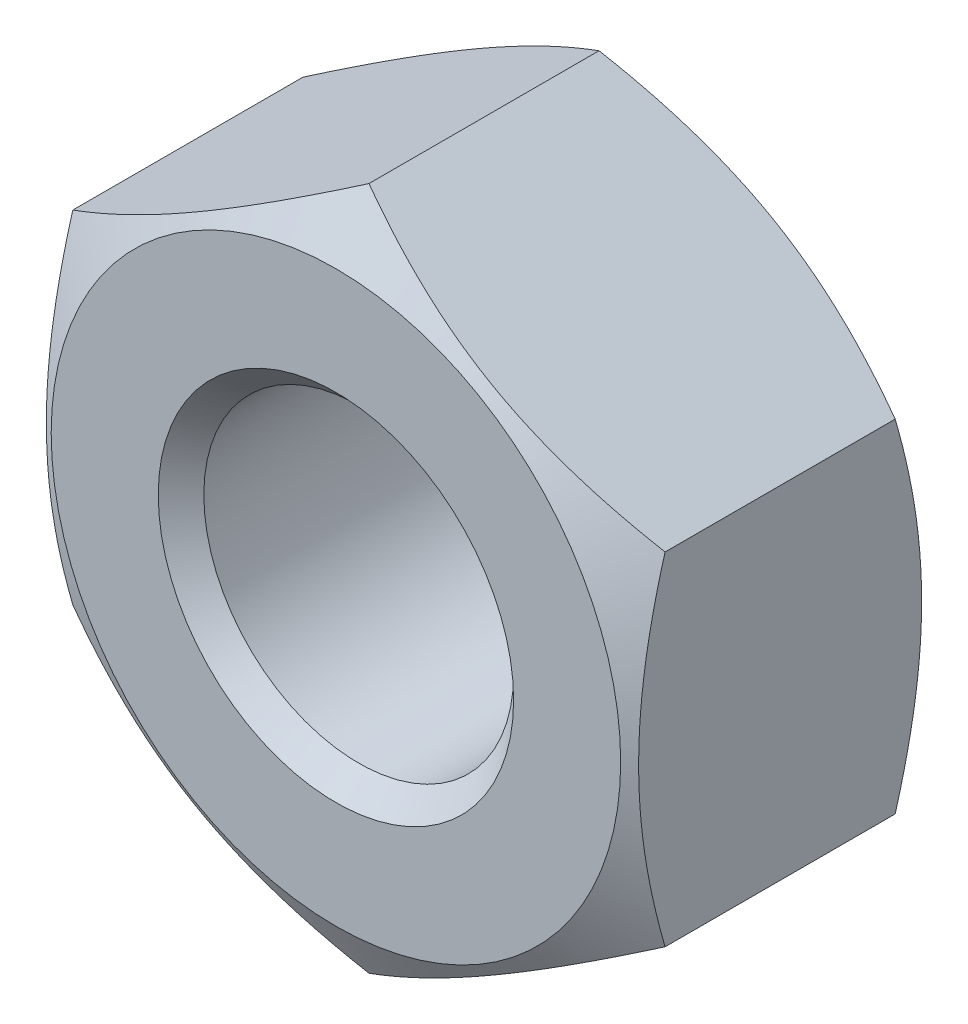
SolidWorks part; units mm, degrees
material "ASTM A36 Steel"
ref_plane "Front" through (0, 0, 0) normal (0, 0, 1) x (1, 0, 0)
ref_plane "Top" through (0, 0, 0) normal (0, 1, 0) x (1, 0, 0)
ref_plane "Right" through (0, 0, 0) normal (1, 0, 0) x (0, 0, -1)
sketch "Sketch1" plane through (0, 0, 0) normal (1, 0, 0) x (0, 0, -1)
  line L0 (0, 6.25) -> (1.0104, 8)
  line L1 (0, 0) -> (6.5, 0) construction
  line L2 (0, 0) -> (0, 6.25)
  line L3 (1.0104, 8) -> (5.4896, 8)
  line L4 (6.5, 0) -> (6.5, 6.25)
  line L5 (6.5, 6.25) -> (5.4896, 8)
  line L6 (0, 0) -> (6.5, 0)
  dimension "D1" = 16
  dimension "D2" = 6.5
  dimension "D3" = 30
  dimension "D4" = 30
  dimension "D5" = 12.5
  dimension "D6" = 12.5
revolve "Revolve1" add sketch "Sketch1" angle 360 about L1
sketch "Sketch2" plane through (0, 0, 0) normal (0, 0, 1) x (1, 0, 0)
  line L1 (0, 7.5056) -> (-6.5, 3.7528)
  line L2 (-6.5, 3.7528) -> (-6.5, -3.7528)
  line L3 (-6.5, -3.7528) -> (0, -7.5056)
  line L4 (0, -7.5056) -> (6.5, -3.7528)
  line L5 (6.5, -3.7528) -> (6.5, 3.7528)
  line L6 (6.5, 3.7528) -> (0, 7.5056)
  circle A0 centre (0, 0) radius 6.5 construction
  circle A1 centre (0, 0) radius 8
  dimension "D1" = 16
  dimension "D2" = 13
  dimension "D3" = 6.5
extrude "Cut-Extrude1" cut sketch "Sketch2" against normal through all
hole_wizard "M8x1.25 Tapped Hole1" positions "Sketch4" profile "Sketch3" tap size "M8x1.25" standard "ANSI Metric" end condition through all
sketch "Sketch4" plane through (0, 0, 0) normal (0, 0, 1) x (1, 0, 0)
  point P0 (0, 0)
sketch "Sketch3" plane through (0, 0, 0) normal (1, 0, 0) x (0, -1, 0)
  line L0 (0, 0) -> (0, 6.5)
  line L1 (0, 6.5) -> (3.4, 6.5)
  line L2 (3.4, 6.5) -> (3.4, 0)
  line L5 (3.4, 0) -> (0, 0)
  line L11 (0, -6.35) -> (0, 107.95) construction
  dimension "Thru Tap Drill Dia." = 6.8
  dimension "Thru Tap Drill Depth" = 6.5
cosmetic thread "Hole Thread1" parameters "D2"=8
chamfer "Chamfer1" distance 0.5 angle 45 2 edges at (3.4, 0, -6.5) (3.4, 0, 0)
